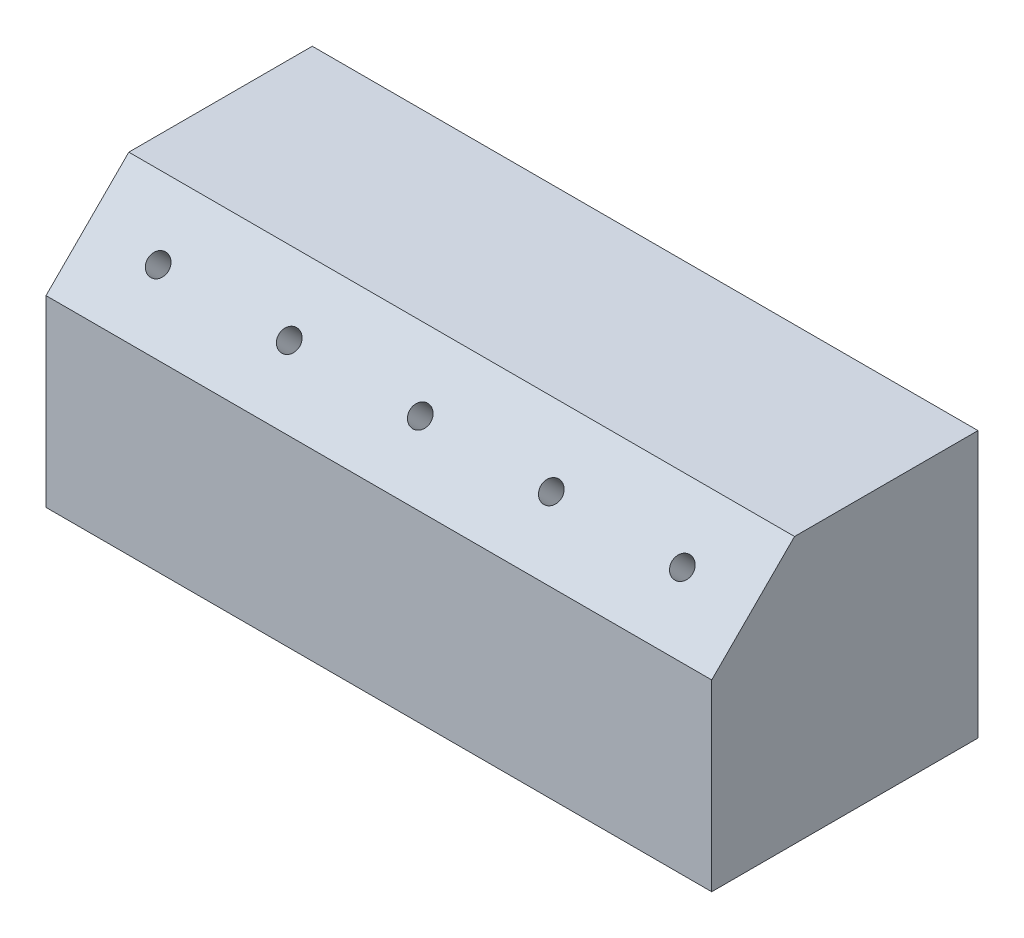
SolidWorks part; units mm, degrees
material "Aleación 6061"
ref_plane "Alzado" through (0, 0, 0) normal (0, 0, 1) x (1, 0, 0)
ref_plane "Planta" through (0, 0, 0) normal (0, 1, 0) x (1, 0, 0)
ref_plane "Vista lateral" through (0, 0, 0) normal (1, 0, 0) x (0, 0, -1)
sketch "Croquis1" plane through (0, 0, 0) normal (1, 0, 0) x (0, 0, -1)
  line L0 (-9.6, 25.4) -> (-25.4, 9.6)
  line L1 (-9.6, 25.4) -> (25.4, 25.4)
  line L2 (-25.4, 9.6) -> (-25.4, -25.4)
  line L3 (-25.4, -25.4) -> (25.4, -25.4)
  line L4 (25.4, 25.4) -> (25.4, -25.4)
  point P0 (0, 0)
  dimension "D1" = 35
  dimension "D2" = 35
  dimension "D3" = 50.8
  dimension "D4" = 50.8
extrude "Saliente-Extruir1" add sketch "Croquis1" along normal mid plane 127
hole_wizard "Taladro roscado 1/4 NPT1" positions "Croquis2" profile "Croquis4" size "1/4" standard "Ansi Inch"
sketch "Croquis2" plane through (63.5, 0, 0) normal (1, 0, 0) x (0, 0, -1)
  point P0 (0, 0)
sketch "Croquis4" plane through (63.5, 0, 0) normal (0, 1, 0) x (0, 0, -1)
  line L0 (0, 0) -> (0, 23.3423)
  line L1 (5.5626, 20) -> (0, 23.3423)
  line L2 (-5.5626, 20) -> (0, 23.3423) construction
  line L3 (5.5626, 20) -> (5.5626, 10.02)
  line L4 (5.5626, 10.02) -> (6.558, 10.02)
  line L5 (6.558, 10.02) -> (6.858, 0)
  line L6 (-6.558, 10.02) -> (-6.858, 0) construction
  line L7 (6.858, 0) -> (0, 0)
  line L8 (0, -6.35) -> (0, 107.95) construction
  line L11 (-5.5626, 10.02) -> (-6.558, 10.02) construction
  dimension "Diámetro de perforador para roscar" = 11.1252
  dimension "Profundidad de perforador para roscar" = 20
  dimension "Diámetro de rosca" = 13.716
  dimension "Ángulo de rosca" = 3.43
  dimension "Profundidad de rosca" = 10.02
  dimension "Ángulo de perforador" = 118
hole_wizard "Taladro roscado 1/4 NPT2" positions "Croquis3D1" profile "Croquis5" size "1/4" standard "Ansi Inch"
sketch3d "Croquis3D1"
  line L0 (-63.5, -25.4, 25.4) -> (-63.5, -25.4, -25.4) construction
  line L1 (-63.5, -25.4, -25.4) -> (-63.5, 25.4, -25.4) construction
  point P0 (-63.5, 0, 0)
  dimension "D1" = 25.4
  dimension "D2" = 25.4
sketch "Croquis5" plane through (-63.5, 0, 0) normal (0, 1, 0) x (0, 0, 1)
  line L0 (0, 0) -> (0, 23.3423)
  line L1 (5.5626, 20) -> (0, 23.3423)
  line L2 (-5.5626, 20) -> (0, 23.3423) construction
  line L3 (5.5626, 20) -> (5.5626, 10.02)
  line L4 (5.5626, 10.02) -> (6.558, 10.02)
  line L5 (6.558, 10.02) -> (6.858, 0)
  line L6 (-6.558, 10.02) -> (-6.858, 0) construction
  line L7 (6.858, 0) -> (0, 0)
  line L8 (0, -6.35) -> (0, 107.95) construction
  line L11 (-5.5626, 10.02) -> (-6.558, 10.02) construction
  dimension "Diámetro de perforador para roscar" = 11.1252
  dimension "Profundidad de perforador para roscar" = 20
  dimension "Diámetro de rosca" = 13.716
  dimension "Ángulo de rosca" = 3.43
  dimension "Profundidad de rosca" = 10.02
  dimension "Ángulo de perforador" = 118
sketch "Croquis6" plane through (0, 0, 0) normal (1, 0, 0) x (0, 0, -1)
  circle A0 centre (0, 0) radius 5
extrude "Cortar-Extruir1" cut sketch "Croquis6" against normal blind 42 and the other way blind 57
sketch "Croquis7" plane through (0, 17.5, 17.5) normal (0, 0.7071, 0.7071) x (1, 0, 0)
  line L0 (0, -27.94) -> (0, 27.94) construction
  circle A0 centre (0, 0) radius 2
  circle A1 centre (25, 0) radius 2
  circle A2 centre (50, 0) radius 2
  circle A3 centre (-50, 0) radius 2
  circle A4 centre (-25, 0) radius 2
  dimension "D1" = 63.5
  dimension "D2" = 3
extrude "Cortar-Extruir2" cut sketch "Croquis7" against normal up to surface (20.1662 mm away)
